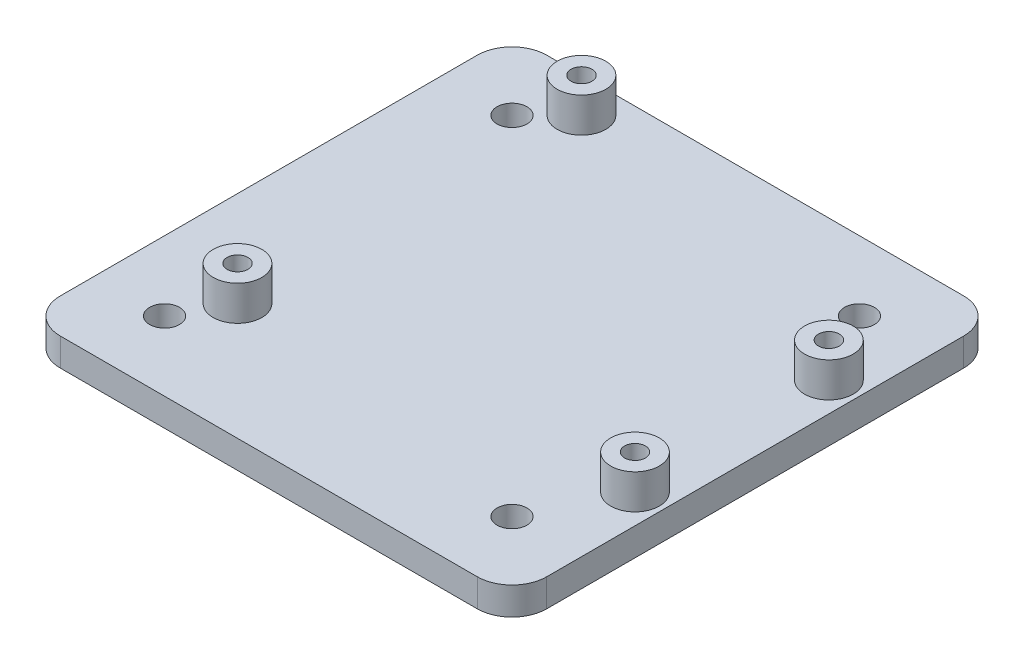
SolidWorks part; units mm, degrees
ref_plane "前基準面" through (0, 0, 0) normal (0, 0, 1) x (1, 0, 0)
ref_plane "上基準面" through (0, 0, 0) normal (0, 1, 0) x (1, 0, 0)
ref_plane "右基準面" through (0, 0, 0) normal (1, 0, 0) x (0, 0, -1)
sketch "草圖2" plane through (0, 0, 0) normal (0, 1, 0) x (1, 0, 0)
  line L0 (-44.1686, 25) -> (69.5299, 25) construction
  line L1 (-35, 35) -> (35, 35)
  line L2 (-35, 35) -> (-35, -35)
  line L3 (-35, -35) -> (35, -35)
  line L4 (35, 35) -> (35, -35)
  line L5 (-35, 35) -> (35, -35) construction
  line L6 (-35, -35) -> (35, 35) construction
  line L7 (69.5299, 25) -> (69.5299, -25) construction
  line L8 (69.5299, -25) -> (-40.5747, -25) construction
  circle A0 centre (-25, 25) radius 2.15
  circle A1 centre (25, 25) radius 2.15
  circle A2 centre (-25, -25) radius 2.15
  circle A3 centre (25, -25) radius 2.15
  point P0 (0, 0)
  dimension "D5" = 4.3
  dimension "D6" = 10
  dimension "D7" = 10
  dimension "D8" = 10
  dimension "D9" = 10
  dimension "D1" = 70
  dimension "D2" = 70
  dimension "D3" = 10
  dimension "D4" = 10
extrude "填料-伸長1" add sketch "草圖2" along normal blind 4
sketch "草圖3" plane through (0, 4, 0) normal (0, 1, 0) x (1, 0, 0)
  line L0 (35, 35) -> (-35, 35) construction
  line L1 (-35, 35) -> (-35, -35) construction
  circle A0 centre (-21.3, -18.2) radius 1.5
  circle A1 centre (-20, 30) radius 1.5
  circle A2 centre (30.8, 14.8) radius 1.5
  circle A3 centre (30.8, -13.1) radius 1.5
  circle A5 centre (-20, 30) radius 3.5
  circle A6 centre (30.8, 14.8) radius 3.5
  circle A7 centre (30.8, -13.1) radius 3.5
  circle A8 centre (-21.3, -18.2) radius 3.5
  dimension "D2" = 5
  dimension "D3" = 48.2
  dimension "D4" = 3
  dimension "D5" = 50.8
  dimension "D6" = 15
  dimension "D7" = 15.2
  dimension "D8" = 27.9
  dimension "D9" = 7
  dimension "D1" = 1.3
extrude "填料-伸長2" add sketch "草圖3" along normal blind 5
fillet "圓角1" radius 5 4 edges at (35, 2, -35) (35, 2, 35) (-35, 2, 35) (-35, 2, -35)
